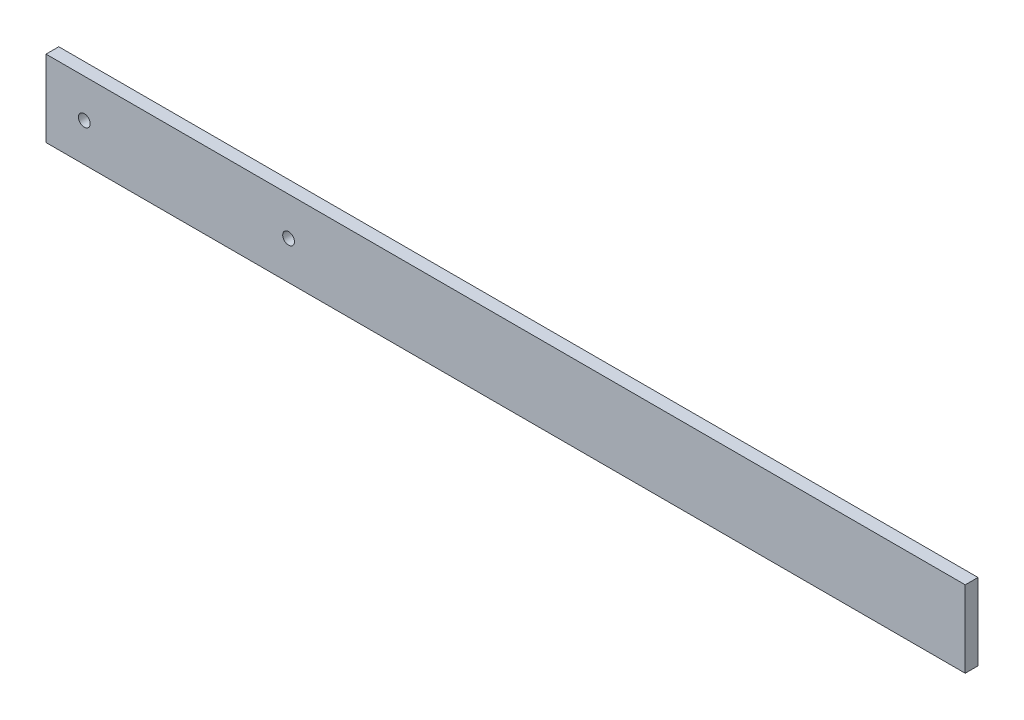
SolidWorks part; units mm, degrees
ref_plane "Front Plane" through (0, 0, 0) normal (0, 0, 1) x (1, 0, 0)
ref_plane "Top Plane" through (0, 0, 0) normal (0, 1, 0) x (1, 0, 0)
ref_plane "Right Plane" through (0, 0, 0) normal (1, 0, 0) x (0, 0, -1)
sketch "Sketch1" plane through (0, 0, 0) normal (0, 0, 1) x (1, 0, 0)
  line L1 (0, 0) -> (228.6, 0)
  line L2 (0, 0) -> (0, 19.05)
  line L3 (0, 19.05) -> (228.6, 19.05)
  line L4 (228.6, 0) -> (228.6, 19.05)
  dimension "D1" = 228.6
  dimension "D2" = 19.05
extrude "Boss-Extrude1" add sketch "Sketch1" along normal blind 3.175
sketch "Sketch2" plane through (0, 0, 3.175) normal (0, 0, 1) x (1, 0, 0)
  line L0 (0, 19.05) -> (0, 0) construction
  circle A0 centre (9.525, 9.525) radius 1.4605
  circle A1 centre (60.325, 9.525) radius 1.4605
  point P6 (0, 9.525)
  dimension "D1" = 50.8
  dimension "D2" = 2.921
  dimension "D3" = 2.921
  dimension "D4" = 9.525
extrude "Cut-Extrude1" cut sketch "Sketch2" against normal through all
